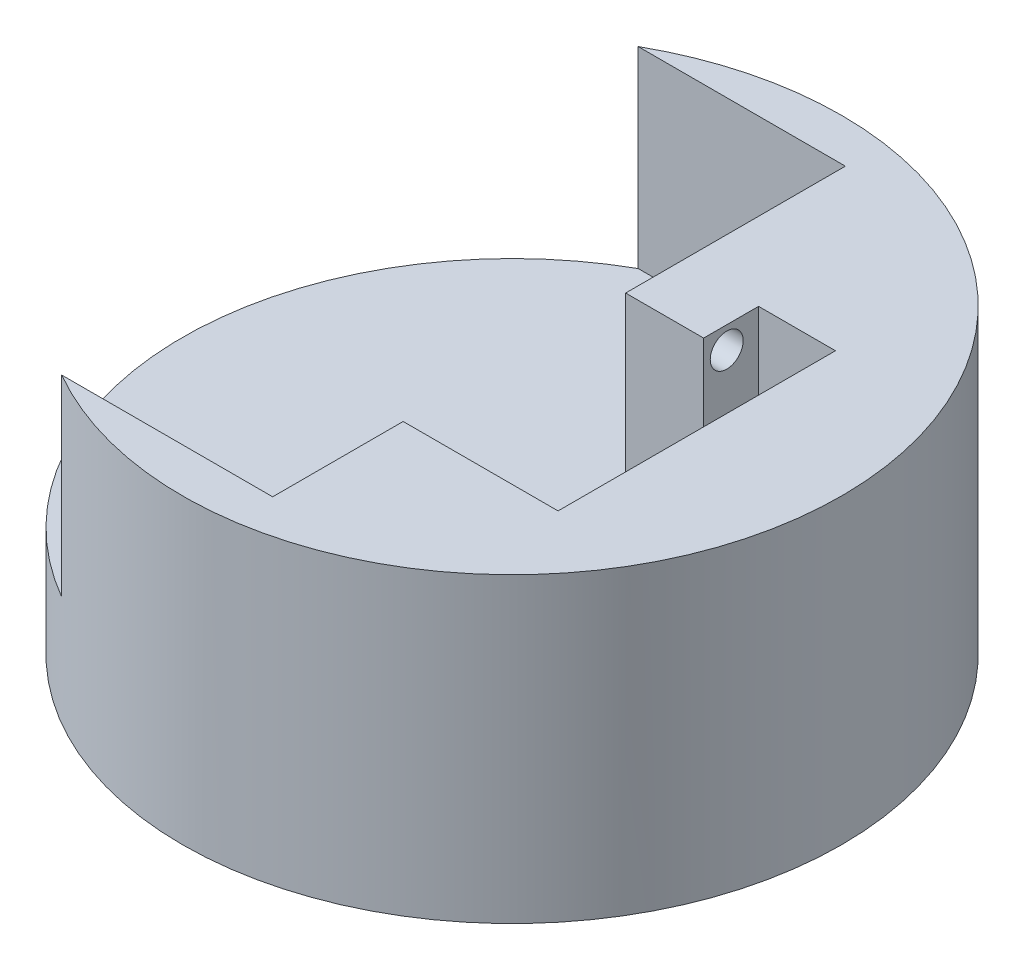
SolidWorks part; units mm, degrees
ref_plane "Front Plane" through (0, 0, 0) normal (0, 0, 1) x (1, 0, 0)
ref_plane "Top Plane" through (0, 0, 0) normal (0, 1, 0) x (1, 0, 0)
ref_plane "Right Plane" through (0, 0, 0) normal (1, 0, 0) x (0, 0, -1)
sketch "Sketch2" plane through (0, 0, 0) normal (0, 1, 0) x (1, 0, 0)
  circle A0 centre (0, 0) radius 60
  dimension "D1" = 120
extrude "Boss-Extrude1" add sketch "Sketch2" along normal blind 30
sketch "Sketch3" plane through (0, 30, 0) normal (0, 1, 0) x (1, 0, 0)
  line L5 (22.5489, 12.3223) -> (8.3489, 12.3223)
  line L12 (5.9689, -51.9337) -> (-19.0311, -51.9337)
  line L13 (8.3489, 12.3223) -> (8.3489, 22.3223)
  line L15 (8.3489, -28.1777) -> (8.3489, -41.1777)
  line L17 (36.5489, 12.3223) -> (36.5489, -28.1777)
  line L18 (36.5489, -28.1777) -> (8.3489, -28.1777)
  line L25 (22.5489, 22.3223) -> (22.5489, 12.3223)
  line L26 (-19.0311, 52.3223) -> (5.9689, 52.3223)
  line L28 (8.3489, 22.3223) -> (8.3489, 52.3223)
  line L29 (8.3489, 52.3223) -> (5.9689, 52.3223)
  line L30 (8.3489, -41.1777) -> (8.3489, -51.9337)
  line L31 (8.3489, -51.9337) -> (5.9689, -51.9337)
  line L32 (36.5489, 12.3223) -> (36.5489, 22.3223)
  line L34 (36.5489, 22.3223) -> (22.5489, 22.3223)
  line L35 (-19.0311, 52.3223) -> (-29.3662, 52.3223)
  line L37 (-29.3662, -51.9337) -> (-19.0311, -51.9337)
  circle A0 centre (0, 0) radius 60 construction
  arc A1 (-29.3662, 52.3223) -> (-29.3662, -51.9337) centre (-29.3662, 0.1943) ccw
  dimension "D3" = 14
  dimension "D4" = 25
  dimension "D5" = 28.2
  dimension "D7" = 30
  dimension "D8" = 13
  dimension "D12" = 40.5
sketch "Sketch9" plane through (0, 0, 0) normal (0, -1, 0) x (-1, 0, 0)
  circle A1 centre (0, 0) radius 60
extrude "Boss-Extrude2" add sketch "Sketch9" along normal blind 10
sketch "Sketch10" plane through (0, -10, 0) normal (0, -1, 0) x (1, 0, 0)
  line L12 (0, 0) -> (9.8461, 0)
  line L13 (9.8461, 0) -> (12.6096, -2.7636)
  line L14 (12.6096, -2.7636) -> (19.0829, -2.7636)
  line L15 (19.0829, -2.7636) -> (20.7278, 1.9383)
  line L16 (20.7278, 1.9383) -> (21.8033, 0.8627)
  line L17 (21.8033, 0.8627) -> (27.7503, 0.8627)
  line L18 (22.3705, -16.9194) -> (23.7511, -14.052)
  line L19 (23.7511, -14.052) -> (25.8025, -14.052)
  line L20 (24.7768, 4.7987) -> (24.7768, -20.2647) construction
  line L21 (28.8258, 1.9383) -> (27.7503, 0.8627)
  line L22 (30.4707, -2.7636) -> (28.8258, 1.9383)
  line L23 (36.944, -2.7636) -> (30.4707, -2.7636)
  line L24 (27.1831, -16.9194) -> (25.8025, -14.052)
  line L25 (39.7076, 0) -> (36.944, -2.7636)
  line L26 (49.5536, 0) -> (39.7076, 0)
  arc A5 (0, 0) -> (9.8461, -10.7598) centre (0, -9.8849) cw
  arc A6 (9.8461, -10.7598) -> (22.3705, -16.9194) centre (8.1311, -30.0595) cw
  arc A7 (39.7076, -10.7598) -> (27.1831, -16.9194) centre (41.4225, -30.0595) ccw
  arc A8 (49.5536, 0) -> (39.7076, -10.7598) centre (49.5536, -9.8849) ccw
  point P19 (24.7768, 0.8627)
  point P23 (24.7768, -14.052)
extrude "Cut-Extrude23" cut sketch "Sketch10" against normal blind 2
sketch "Sketch15" plane through (0, -10, 0) normal (0, -1, 0) x (-1, 0, 0)
  circle A0 centre (0, 0) radius 60
extrude "Boss-Extrude5" add sketch "Sketch15" along normal blind 15
extrude "Cut-Extrude25" cut sketch "Sketch3" against normal blind 35
sketch "Sketch17" plane through (8.3489, 0, 0) normal (-1, 0, 0) x (0, 0, 1)
  line L0 (-12.3223, 30) -> (-52.3223, 30) construction
  line L1 (-12.3223, -5) -> (-12.3223, 30) construction
  line L2 (28.1777, -5) -> (28.1777, 30) construction
  line L3 (51.9337, 30) -> (28.1777, 30) construction
  circle A0 centre (-16.5223, 26) radius 3
  circle A1 centre (32.3777, 26) radius 3
  dimension "D1" = 6
  dimension "D4" = 6
  dimension "D2" = 4
  dimension "D3" = 4.2
  dimension "D5" = 4.2
  dimension "D6" = 4
extrude "Cut-Extrude26" cut sketch "Sketch17" against normal blind 23
sketch "Sketch18" plane through (0, -25, 0) normal (0, -1, 0) x (1, 0, 0)
  circle A0 centre (0, 0) radius 52.2586
extrude "Cut-Extrude27" cut sketch "Sketch18" against normal blind 5
sketch "Sketch19" plane through (8.3489, 0, 0) normal (-1, 0, 0) x (0, 0, 1)
  text T0 "BATARM"
extrude "Boss-Extrude7" add sketch "Sketch19" along normal blind 2
